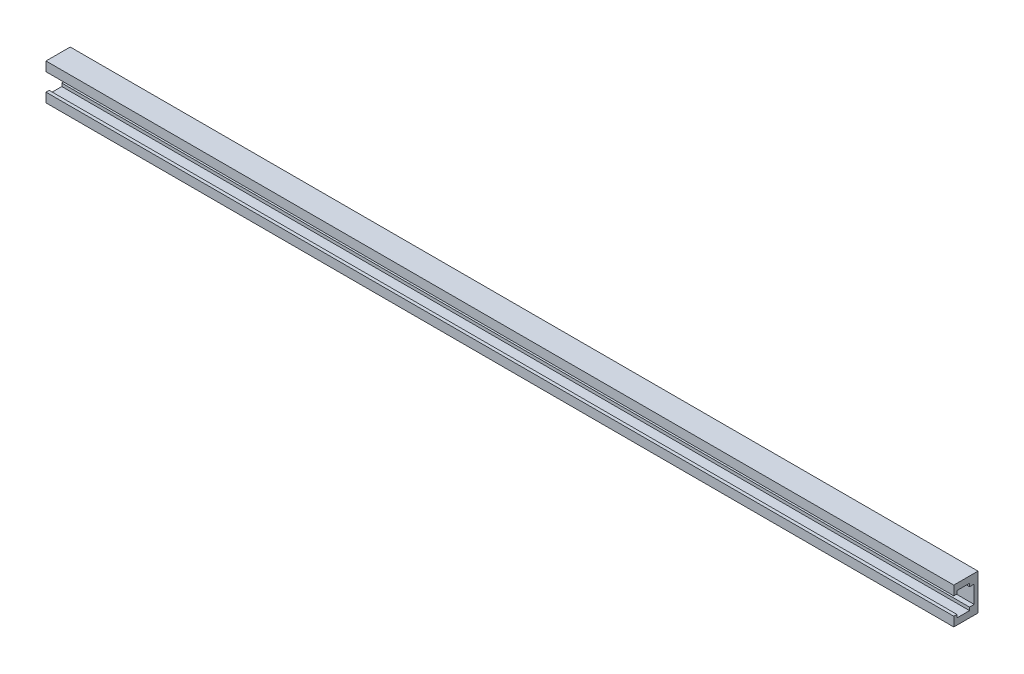
SolidWorks part; units mm, degrees
ref_plane "Front" through (0, 0, 0) normal (0, 0, 1) x (1, 0, 0)
ref_plane "Top" through (0, 0, 0) normal (0, 1, 0) x (1, 0, 0)
ref_plane "Right" through (0, 0, 0) normal (1, 0, 0) x (0, 0, -1)
sketch "Sketch1" plane through (0, 0, 0) normal (1, 0, 0) x (0, 0, -1)
  line L1 (0, 9.144) -> (-12.192, 9.144)
  line L2 (0, 9.144) -> (0, -9.144)
  line L3 (0, -9.144) -> (-12.192, -9.144)
  line L4 (-12.192, 9.144) -> (-12.192, -9.144)
  point P4 (0, 0)
  dimension "D1" = 18.288
  dimension "D2" = 12.192
sketch "Sketch2" plane through (0, 0, 0) normal (1, 0, 0) x (0, 0, -1)
  line L0 (0, 9.144) -> (-12.192, 9.144)
  line L1 (-12.192, 9.144) -> (-12.192, 4.445)
  line L2 (-12.192, 9.144) -> (-12.192, -9.144) construction
  line L3 (-12.192, 4.445) -> (-10.6045, 4.445)
  line L4 (-10.6045, 4.445) -> (-10.6045, 5.969)
  line L5 (-10.6045, 5.969) -> (-4.2545, 5.969)
  line L6 (-4.2545, 5.969) -> (-4.2545, 4.445)
  line L7 (-4.2545, 4.445) -> (-1.905, 4.445)
  line L8 (-1.905, 4.445) -> (-1.905, -4.445)
  line L9 (-1.905, -4.445) -> (-4.2545, -4.445)
  line L10 (-4.2545, -4.445) -> (-4.2545, -5.969)
  line L11 (-4.2545, -5.969) -> (-10.6045, -5.969)
  line L12 (-10.6045, -5.969) -> (-10.6045, -4.445)
  line L13 (-10.6045, -4.445) -> (-12.192, -4.445)
  line L14 (-12.192, -4.445) -> (-12.192, -9.144)
  line L15 (-12.192, -9.144) -> (0, -9.144)
  line L16 (0, -9.144) -> (0, 9.144)
  line L17 (0, 0) -> (-19.0377, 0) construction
  point P25 (-1.905, 0)
  dimension "D1" = 1.905
  dimension "D2" = 8.89
  dimension "D3" = 3.175
  dimension "D4" = 6.35
  dimension "D5" = 8.89
  dimension "D6" = 1.5875
extrude "Boss-Extrude1" add sketch "Sketch2" along normal mid plane 457.2
sketch "Sketch3" plane through (0, 0, 1.905) normal (0, 0, 1) x (1, 0, 0)
  line L0 (0, 0) -> (38.1, 0) construction
  line L1 (0, 0) -> (0, 27.0833) construction
  circle A0 centre (38.1, 0) radius 2.413
  dimension "D2" = 4.826
  dimension "D1" = 76.2
extrude "Cut-Extrude1" cut sketch "Sketch3" against normal up to surface (1.905 mm away) up to face at (0, 0, 0)
pattern_linear "LPattern1" count 3 spacing 76.2 along (1, 0, 0) of "Cut-Extrude1"
other "SurfaceCut1"
mirror "Mirror1" about plane through (0, 0, 0) normal (1, 0, 0) of bodies 112
